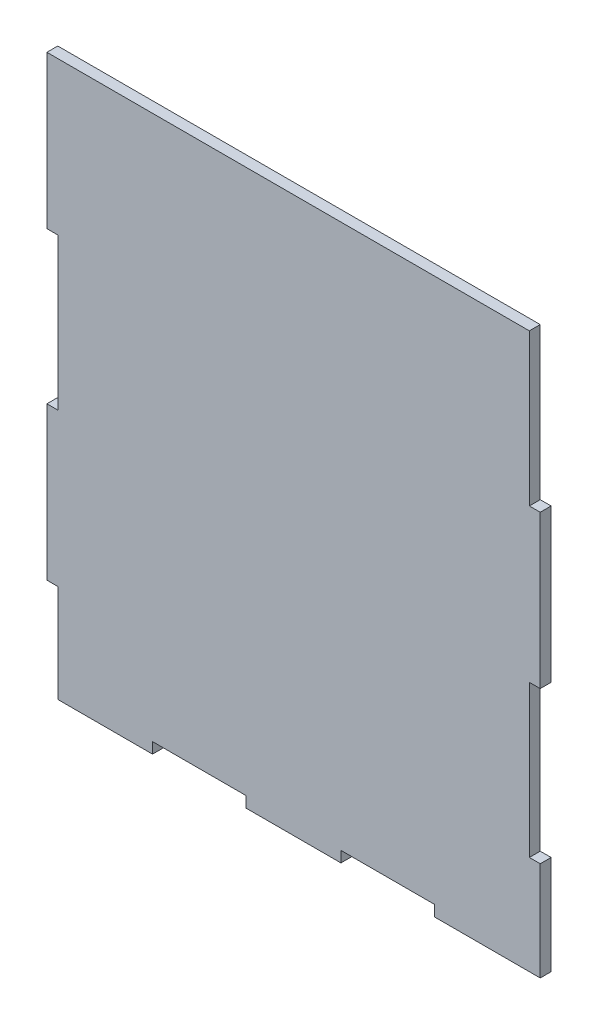
SolidWorks part; units mm, degrees
ref_plane "Front Plane" through (0, 0, 0) normal (0, 0, 1) x (1, 0, 0)
ref_plane "Top Plane" through (0, 0, 0) normal (0, 1, 0) x (1, 0, 0)
ref_plane "Right Plane" through (0, 0, 0) normal (1, 0, 0) x (0, 0, -1)
sketch "Sketch1" plane through (0, 0, 0) normal (0, 0, 1) x (1, 0, 0)
  line L0 (65.7414, 34.0484) -> (65.7414, -7.7588) construction
  line L1 (65.7414, -7.7588) -> (65.7414, -8.0588) construction
  line L2 (68.7414, -77.1445) -> (65.7414, -77.1445)
  line L3 (65.7414, -77.1445) -> (39.6214, -77.1445)
  line L4 (-12.3186, -74.1445) -> (13.5014, -74.1445) construction
  line L5 (13.5014, -74.1445) -> (13.8014, -74.1445) construction
  line L6 (65.7414, 75.8555) -> (-64.2586, -74.1445) construction
  line L7 (65.7414, -74.1445) -> (-67.2586, 75.8555) construction
  line L70 (65.7414, 75.8555) -> (65.7414, 34.0484)
  line L71 (65.7414, 34.0484) -> (68.7414, 34.0484)
  line L72 (68.7414, 34.0484) -> (68.7414, -8.0588)
  line L73 (68.7414, -8.0588) -> (65.7414, -8.0588)
  line L74 (65.7414, -8.0588) -> (65.7414, -49.8659)
  line L75 (65.7414, -49.8659) -> (68.7414, -49.8659)
  line L127 (39.6214, -74.1445) -> (39.6214, -77.1445)
  line L128 (-12.3186, -77.1445) -> (13.8014, -77.1445)
  line L129 (13.8014, -77.1445) -> (13.8014, -74.1445)
  line L131 (-12.3186, -74.1445) -> (-12.3186, -77.1445)
  line L132 (-64.2586, -77.1445) -> (-38.1386, -77.1445)
  line L133 (-38.1386, -77.1445) -> (-38.1386, -74.1445)
  line L136 (-38.1386, -74.1445) -> (-12.3186, -74.1445)
  line L137 (13.8014, -74.1445) -> (39.6214, -74.1445)
  line L138 (68.7414, -77.1445) -> (68.7414, -49.8659)
  line L139 (65.7414, 75.8555) -> (-67.2586, 75.8555)
  line L140 (-67.2586, 75.8555) -> (-67.2586, 33.7484)
  line L141 (-67.2586, 33.7484) -> (-64.2586, 33.7484)
  line L142 (-64.2586, 33.7484) -> (-64.2586, -8.0588)
  line L143 (-64.2586, -8.0588) -> (-67.2586, -8.0588)
  line L144 (-67.2586, -8.0588) -> (-67.2586, -50.1659)
  line L145 (-67.2586, -50.1659) -> (-64.2586, -50.1659)
  line L146 (-64.2586, -77.1445) -> (-64.2586, -50.1659)
  point P1 (0, 0)
  point P16 (99.0774, -83.1828)
  point P18 (0, 0)
  dimension "D1" = 153
  dimension "D2" = 42.1071
  dimension "D3" = 0.3
  dimension "D4" = 3
  dimension "D5" = 130
  dimension "D6" = 0.3
extrude "Boss-Extrude1" add sketch "Sketch1" along normal blind 3
